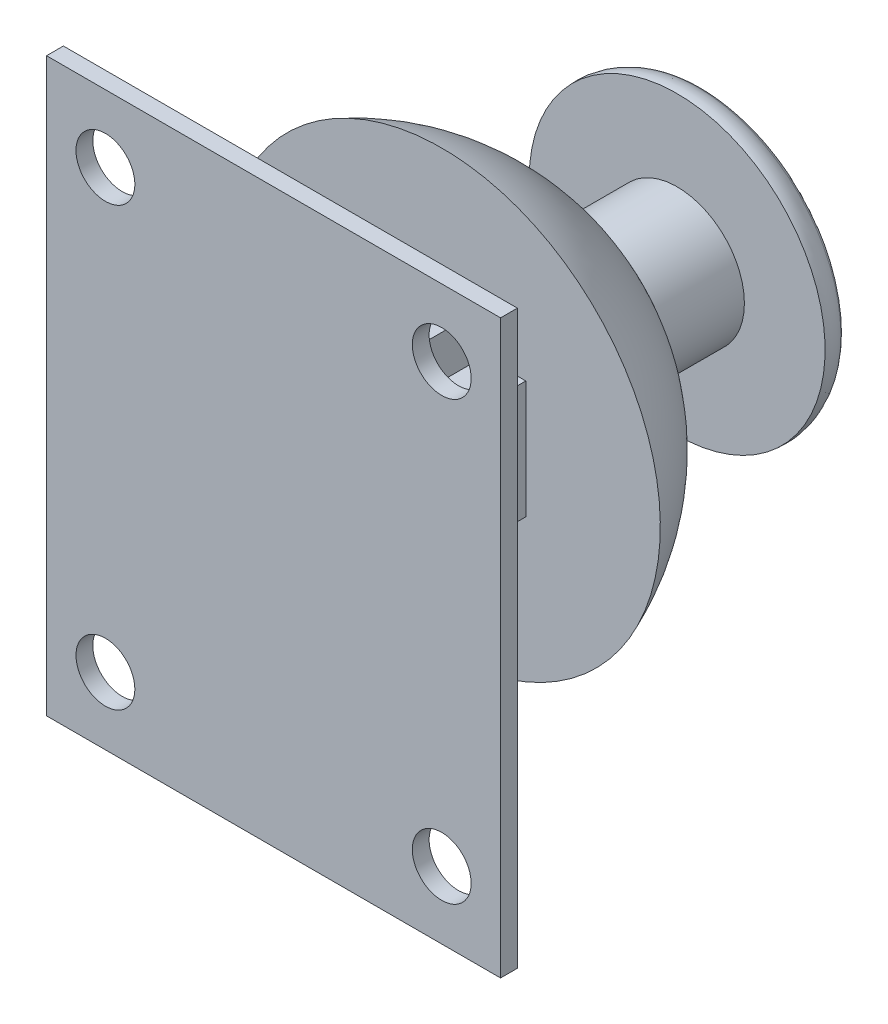
SolidWorks part; units mm, degrees
ref_plane "前视基准面" through (0, 0, 0) normal (0, 0, 1) x (1, 0, 0)
ref_plane "上视基准面" through (0, 0, 0) normal (0, 1, 0) x (1, 0, 0)
ref_plane "右视基准面" through (0, 0, 0) normal (1, 0, 0) x (0, 0, -1)
other "Configuration Table"
sketch "草图1" plane through (0, 0, 0) normal (0, 0, 1) x (1, 0, 0)
  line L0 (-15.6451, 0) -> (15.3187, 0) construction
  line L1 (0, 15.4051) -> (0, -15.6053) construction
  line L2 (-13.5, 17) -> (13.5, 17)
  line L3 (13.5, 17) -> (13.5, -17)
  line L4 (-13.5, 17) -> (-13.5, -17)
  line L5 (-13.5, -17) -> (13.5, -17)
  circle A0 centre (10, 13) radius 1.75
  circle A1 centre (-10, 13) radius 1.75
  circle A2 centre (10, -13) radius 1.75
  circle A3 centre (-10, -13) radius 1.75
  point P11 (0, 17)
  point P17 (13.5, 0)
  point P18 (-13.5, 0)
  dimension "D3" = 26
  dimension "D4" = 20
  dimension "D5" = 3.5
  dimension "D1" = 27
  dimension "D2" = 34
extrude "凸台-拉伸1" add sketch "草图1" along normal blind 1
sketch "草图2" plane through (0, 0, 0) normal (0, 0, -1) x (-1, 0, 0)
  line L0 (1, 21.074) -> (1, -22.2701) construction
  line L1 (-18.2514, 0) -> (25.5711, 0) construction
  line L2 (12, 3.5) -> (12, -3.5)
  line L3 (12, 0) -> (12, 3.5)
  line L4 (9.5, 6) -> (-1.5, 6)
  line L8 (9.5, 6) -> (9.5, 3.5)
  line L9 (9.5, 3.5) -> (12, 3.5)
  line L10 (-1.5, 6) -> (-1.5, 3.5)
  line L11 (13.5, 17) -> (13.5, -17) construction
  line L12 (-1.5, 3.5) -> (-4, 3.5)
  line L13 (-4, 3.5) -> (-4, -3.5)
  line L14 (9.5, -3.5) -> (12, -3.5)
  line L15 (9.5, -6) -> (9.5, -3.5)
  line L16 (9.5, -6) -> (-1.5, -6)
  line L17 (-1.5, -6) -> (-1.5, -3.5)
  line L18 (-1.5, -3.5) -> (-4, -3.5)
  point P15 (-4, 0)
  point P22 (-4, 0)
  dimension "D1" = 1
  dimension "D2" = 2.5
  dimension "D3" = 1.5
  dimension "D4" = 2.5
  dimension "D5" = 2.5
  dimension "D6" = 2.5
  dimension "D7" = 6
  dimension "D8" = 16
extrude "凸台-拉伸2" add sketch "草图2" along normal blind 10
ref_plane "基准面1" through (-1, 0, 0) normal (1, 0, 0) x (0, 0, -1)
sketch "草图3" plane through (-1, 0, 0) normal (1, 0, 0) x (0, 0, -1)
  line L0 (17.702, 0) -> (-6.8947, 0) construction
  line L1 (10, -13) -> (10, 0)
  line L2 (10, 3.5) -> (10, -3.5) construction
  line L3 (18.8038, 0) -> (10, 0)
  arc A0 (10, -13) -> (18.8038, 0) centre (4.8038, 0) ccw
  point P6 (0, 0)
  dimension "D2" = 14
  dimension "D1" = 13
revolve "旋转1" add sketch "草图3" angle 360 about L0
ref_plane "基准面2" through (0, 0, -18) normal (0, 0, 1) x (1, 0, 0)
sketch "草图4" plane through (0, 0, -18) normal (0, 0, 1) x (1, 0, 0)
  circle A0 centre (-1, 0) radius 4
  circle A1 centre (-1, 0) radius 13
  circle A2 centre (-1, 0) radius 13 construction
  dimension "D2" = 8
  dimension "D1" = 0
extrude "凸台-拉伸3" add sketch "草图4" against normal blind 6
sketch "草图5" plane through (-1, 0, 0) normal (1, 0, 0) x (0, 0, -1)
  line L0 (28.9674, 0) -> (11.5844, 0) construction
  line L1 (24, 0) -> (24, -8.8)
  line L2 (24, -4) -> (24, 4) construction
  line L3 (24, 0) -> (27, 0)
  arc A0 (25.5, -8.3) -> (24, -8.8) centre (24.2386, -7.0159) cw
  arc A1 (27, 0) -> (25.5, -8.3) centre (5.8049, -0.4551) cw
  point P7 (25.5, -8.3)
  point P10 (27, 0)
  dimension "D5" = 21.2
  dimension "D6" = 1.8
  dimension "D1" = 1.5
  dimension "D2" = 0.5
  dimension "D3" = 3
  dimension "D4" = 8.8
revolve "旋转3" add sketch "草图5" angle 360 about L0
fillet "圆角1" radius 1 1 edges at (-9.3, 0, -25.5)
